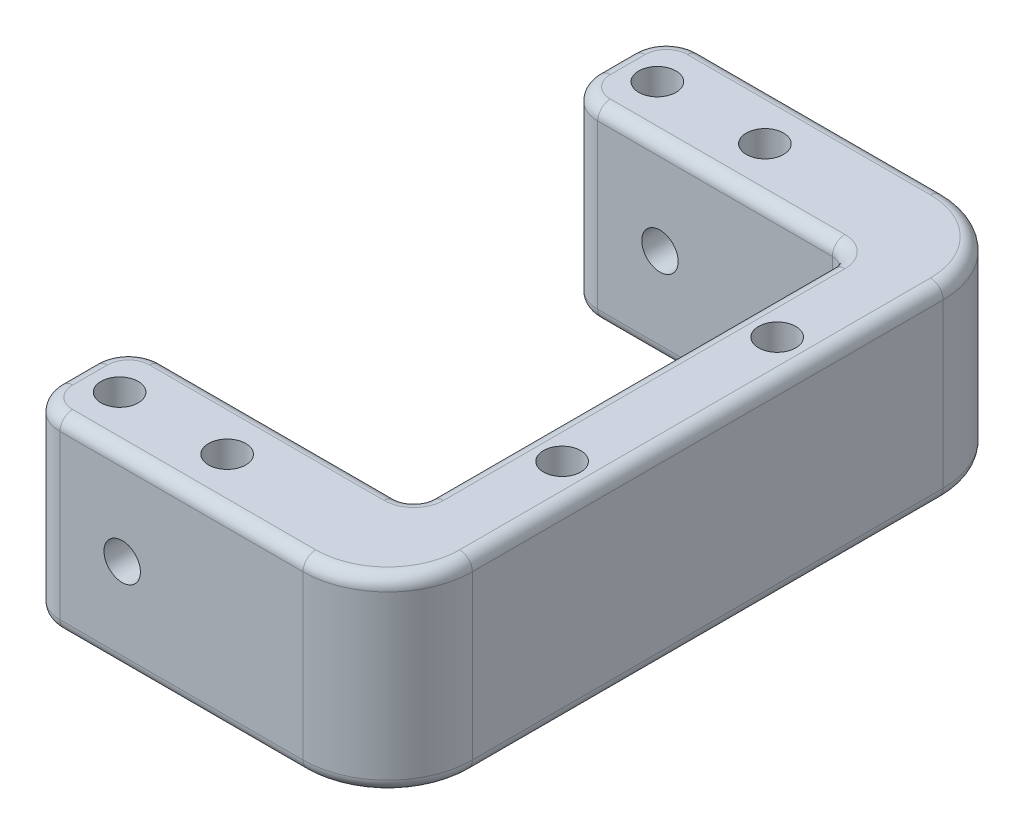
SolidWorks part; units mm, degrees
ref_plane "Front Plane" through (0, 0, 0) normal (0, 0, 1) x (1, 0, 0)
ref_plane "Top Plane" through (0, 0, 0) normal (0, 1, 0) x (1, 0, 0)
ref_plane "Right Plane" through (0, 0, 0) normal (1, 0, 0) x (0, 0, -1)
sketch "Sketch1" plane through (0, 0, 0) normal (0, 1, 0) x (1, 0, 0)
  line L1 (-5, 6.0452) -> (28.7, 6.0452)
  line L2 (-5, 6.0452) -> (-5, -6.0452)
  line L3 (-5, -6.0452) -> (37.7, -6.0452)
  line L8 (28.7, 6.0452) -> (28.7, 57.4548)
  line L9 (37.7, 69.5452) -> (-5, 69.5452)
  line L10 (37.7, 69.5452) -> (37.7, -6.0452)
  line L11 (28.7, 57.4548) -> (-5, 57.4548)
  line L12 (-5, 69.5452) -> (-5, 57.4548)
  circle A0 centre (0, 0) radius 2.2
  circle A1 centre (12.7, 0) radius 2.2
  circle A2 centre (12.7, 63.5) radius 2.2
  circle A3 centre (0, 63.5) radius 2.2
  circle A4 centre (33.2, 44.45) radius 2.2
  circle A5 centre (33.2, 19.05) radius 2.2
  point P9 (-5, 63.5)
  point P19 (28.7, 57.4548)
  point P20 (28.7, 6.0452)
  point P24 (28.7, 31.75)
  point P27 (-5, 0)
  dimension "D1" = 4.4
  dimension "D11" = 4.5
  dimension "D2" = 12.7
  dimension "D3" = 63.5
  dimension "D4" = 6.0452
  dimension "D5" = 6.0452
  dimension "D6" = 9
  dimension "D7" = 5
  dimension "D8" = 16
  dimension "D9" = 25.4
  dimension "D10" = 12.7
extrude "Boss-Extrude1" add sketch "Sketch1" along normal blind 22.2504 contours L9 L12 L11 L8 L1 L2 L3 L10 A3 A2 A1 A0
fillet "Fillet1" radius 10 2 edges at (37.7, 11.1252, -69.5452) (37.7, 11.1252, 6.0452)
fillet "Fillet2" radius 2 2 edges at (28.7, 11.1252, -57.4548) (28.7, 11.1252, -6.0452)
fillet "Fillet3" radius 4 4 edges at (-5, 11.1252, -69.5452) (-5, 11.1252, -57.4548) (-5, 11.1252, -6.0452) (-5, 11.1252, 6.0452)
fillet "Fillet4" radius 1.5 32 edges at (-3.8284, 0, -4.8736) (12.85, 0, -6.0452) (28.1142, 0, -6.631) (28.7, 0, -31.75) (28.1142, 0, -56.869) (12.85, 0, -57.4548) (-3.8284, 0, -58.6264) (-3.8284, 0, -68.3736) (13.35, 0, -69.5452) (34.7711, 0, -66.6163) (37.7, 0, -31.75) (-3.8284, 22.2504, -4.8736) (12.85, 22.2504, -6.0452) (28.1142, 22.2504, -6.631) (28.7, 22.2504, -31.75) (28.1142, 22.2504, -56.869) (12.85, 22.2504, -57.4548) (-3.8284, 22.2504, -58.6264) (-3.8284, 22.2504, -68.3736) (13.35, 22.2504, -69.5452) (34.7711, 22.2504, -66.6163) (37.7, 22.2504, -31.75) (-3.8284, 0, 4.8736) (34.7711, 0, 3.1163) (-3.8284, 22.2504, 4.8736) (34.7711, 22.2504, 3.1163) (13.35, 0, 6.0452) (13.35, 22.2504, 6.0452) (-5, 0, 0) (-5, 0, -63.5) (-5, 22.2504, 0) (-5, 22.2504, -63.5)
sketch "Sketch2" plane through (0, 0, 6.0452) normal (0, 0, 1) x (1, 0, 0)
  line L0 (14.9, 22.2504) -> (10.5, 22.2504) construction
  line L1 (2.2, 22.2504) -> (-2.2, 22.2504) construction
  line L2 (14.9, 22.2504) -> (10.5, 22.2504)
  line L3 (2.2, 22.2504) -> (-2.2, 22.2504)
  line L4 (-1, 20.7504) -> (-1, 1.5) construction
  line L5 (-1, 20.7504) -> (-1, 1.5)
  circle A0 centre (6.35, 11.1252) radius 2.15
  point P4 (12.7, 22.2504)
  point P6 (0, 22.2504)
  point P10 (-1, 11.1252)
  point P11 (0, 0)
  dimension "D1" = 4.3
  dimension "D2" = 6.35
extrude "Cut-Extrude1" cut sketch "Sketch2" against normal through all contours A0
